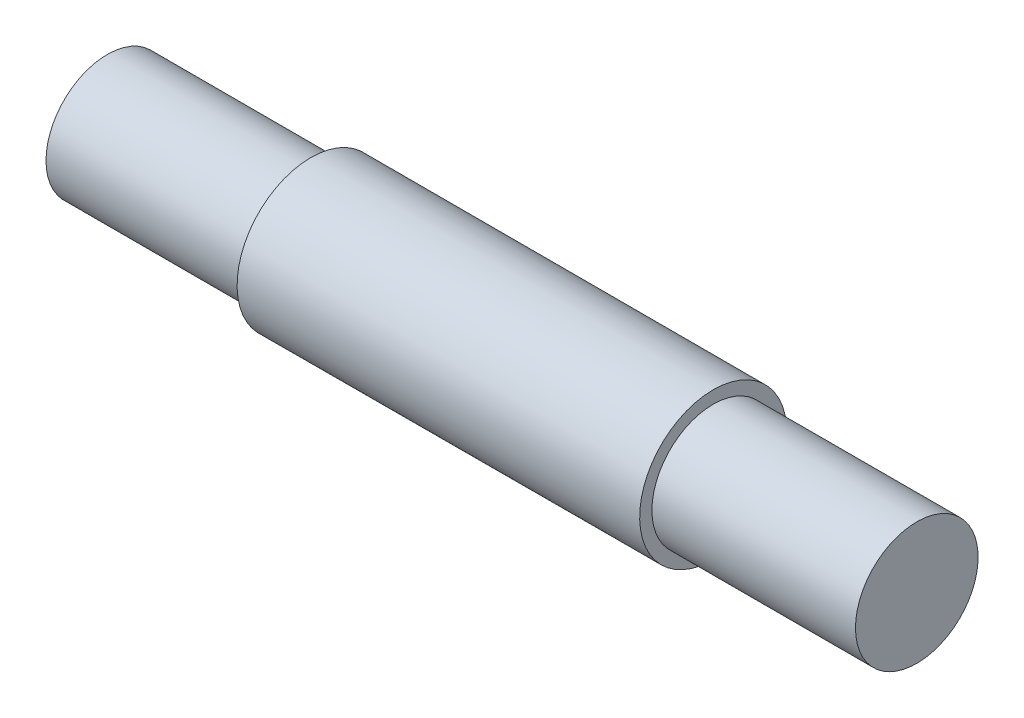
SolidWorks part; units mm, degrees
ref_plane "Front Plane" through (0, 0, 0) normal (0, 0, 1) x (1, 0, 0)
ref_plane "Top Plane" through (0, 0, 0) normal (0, 1, 0) x (1, 0, 0)
ref_plane "Right Plane" through (0, 0, 0) normal (1, 0, 0) x (0, 0, -1)
sketch "Sketch1" plane through (0, 0, 0) normal (0, 0, 1) x (1, 0, 0)
  line L0 (-165, 0) -> (165, 0) construction
  line L1 (-165, 0) -> (-165, 25)
  line L2 (-165, 25) -> (165, 25)
  line L3 (165, 25) -> (165, 0)
  line L4 (-165, 0) -> (165, 0)
  point P5 (165, 12.5)
  dimension "D1" = 330
  dimension "D2" = 25
  dimension "D3" = 165
revolve "Revolve1" add sketch "Sketch1" angle 360 about L0
sketch "Sketch2" plane through (0, 0, 0) normal (0, 0, 1) x (1, 0, 0)
  line L0 (-82, 0) -> (-82, 30.1197)
  line L1 (-82, 30.1197) -> (82, 30.1197)
  line L2 (82, 30.1197) -> (82, 0.1197)
  line L3 (82, 0.1197) -> (-82, 0) construction
  line L4 (-82, 0) -> (82, 0.1197)
  dimension "D1" = 164
  dimension "D2" = 30
  dimension "D3" = 82
revolve "Revolve2" add sketch "Sketch2" angle 360 about L3
